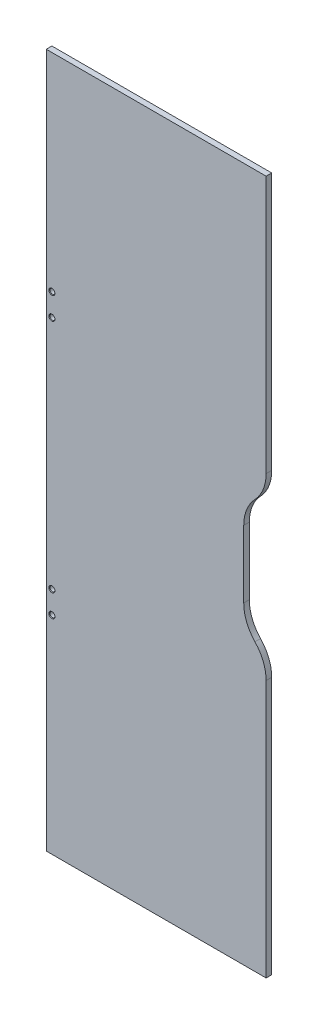
SolidWorks part; units mm, degrees
material "Beech"
ref_plane "Front Plane" through (0, 0, 0) normal (0, 0, 1) x (1, 0, 0)
ref_plane "Top Plane" through (0, 0, 0) normal (0, 1, 0) x (1, 0, 0)
ref_plane "Right Plane" through (0, 0, 0) normal (1, 0, 0) x (0, 0, -1)
sketch "Sketch1" plane through (0, 0, 0) normal (0, 0, 1) x (1, 0, 0)
  line L0 (55.499, 787.4) -> (55.499, 0) construction
  line L1 (42.799, 0) -> (292.1, 0)
  line L2 (42.799, 0) -> (42.799, 787.4)
  line L3 (42.799, 787.4) -> (292.1, 787.4)
  line L4 (292.1, 0) -> (292.1, 787.4)
  line L5 (38.1, 787.4) -> (38.1, 0) construction
  dimension "D1" = 292.1
  dimension "D2" = 787.4
  dimension "D3" = 38.1
  dimension "D4" = 17.399
  dimension "D5" = 12.7
extrude "Boss-Extrude1" add sketch "Sketch1" along normal blind 6.35
hole_wizard "#10 Clearance Hole1" positions "Sketch2" profile "Sketch3" hole size "#10" standard "ANSI Inch" end condition through all
sketch "Sketch2" plane through (0, 0, 6.35) normal (0, 0, 1) x (1, 0, 0)
  line L1 (42.799, 558.8) -> (55.499, 558.8) construction
  line L2 (42.799, 558.8) -> (42.799, 520.7) construction
  line L3 (42.799, 520.7) -> (55.499, 520.7) construction
  line L4 (55.499, 558.8) -> (55.499, 520.7) construction
  line L7 (42.799, 266.7) -> (55.499, 266.7) construction
  line L8 (42.799, 266.7) -> (42.799, 228.6) construction
  line L9 (42.799, 228.6) -> (55.499, 228.6) construction
  line L10 (55.499, 266.7) -> (55.499, 228.6) construction
  line L11 (42.799, 787.4) -> (42.799, 0) construction
  line L12 (292.1, 787.4) -> (42.799, 787.4) construction
  line L14 (49.149, 552.45) -> (49.149, 527.05) construction
  line L16 (49.149, 260.35) -> (49.149, 234.95) construction
  point P0 (49.149, 552.45)
  point P2 (49.149, 527.05)
  point P4 (49.149, 260.35)
  point P6 (49.149, 234.95)
  point P82 (49.149, 228.6)
  point P84 (42.799, 247.65)
  point P85 (49.149, 247.65)
  point P86 (42.799, 539.75)
  point P87 (49.149, 539.75)
  dimension "D1" = 228.6
  dimension "D2" = 228.6
  dimension "D3" = 6.35
  dimension "D4" = 12.7
  dimension "D5" = 38.1
sketch "Sketch3" plane through (49.149, 552.45, 6.35) normal (1, 0, 0) x (0, -1, 0)
  line L0 (0, 0) -> (0, 6.35)
  line L1 (0, 6.35) -> (2.8067, 6.35)
  line L2 (2.8067, 6.35) -> (2.8067, 0.635)
  line L3 (2.8067, 0.635) -> (3.4417, 0)
  line L5 (3.4417, 0) -> (0, 0)
  line L6 (-2.8067, 0.635) -> (-3.4417, 0) construction
  line L11 (0, -6.35) -> (0, 107.95) construction
  dimension "Thru Hole Dia." = 5.6134
  dimension "Thru Hole Depth" = 6.35
  dimension "Near C'Sink Dia." = 6.8834
  dimension "Near C'Sink Angle" = 90
hole_wizard "#10 Clearance Hole2" positions "Sketch4" profile "Sketch5" hole size "#10" standard "ANSI Inch"
sketch "Sketch4" plane through (0, 0, 6.35) normal (0, 0, 1) x (1, 0, 0)
  line L0 (266.7, 444.5) -> (266.7, 342.9) construction
  line L2 (292.1, 0) -> (292.1, 787.4) construction
  point P0 (266.7, 444.5)
  point P2 (266.7, 342.9)
  point P10 (292.1, 393.7)
  point P11 (266.7, 393.7)
  dimension "D1" = 101.6
  dimension "D2" = 25.4
sketch "Sketch5" plane through (266.7, 444.5, 6.35) normal (1, 0, 0) x (0, -1, 0)
  line L0 (0, 0) -> (0, 6.35)
  line L1 (0, 6.35) -> (2.8067, 6.35)
  line L2 (2.8067, 6.35) -> (2.8067, 0.635)
  line L3 (2.8067, 0.635) -> (3.4417, 0)
  line L5 (3.4417, 0) -> (0, 0)
  line L6 (-2.8067, 0.635) -> (-3.4417, 0) construction
  line L11 (0, -6.35) -> (0, 107.95) construction
  dimension "Thru Hole Dia." = 5.6134
  dimension "Thru Hole Depth" = 6.35
  dimension "Near C'Sink Dia." = 6.8834
  dimension "Near C'Sink Angle" = 90
sketch "Sketch6" plane through (0, 0, 6.35) normal (0, 0, 1) x (1, 0, 0)
  line L0 (292.1, 495.3) -> (304.8, 495.3)
  line L1 (292.1, 0) -> (292.1, 787.4) construction
  line L2 (304.8, 495.3) -> (304.8, 292.1)
  line L3 (304.8, 292.1) -> (292.1, 292.1)
  line L4 (266.7, 355.6) -> (266.7, 431.8)
  arc A0 (292.1, 292.1) -> (279.4, 323.85) centre (246.0625, 292.1) ccw
  arc A1 (279.4, 323.85) -> (266.7, 355.6) centre (312.7375, 355.6) cw
  arc A2 (266.7, 431.8) -> (279.4, 463.55) centre (312.7375, 431.8) cw
  arc A3 (279.4, 463.55) -> (292.1, 495.3) centre (246.0625, 495.3) ccw
  point P14 (0, 0)
  point P15 (292.1, 393.7)
  point P16 (266.7, 393.7)
  point P17 (304.8, 393.7)
  dimension "D1" = 25.4
  dimension "D2" = 12.7
  dimension "D3" = 76.2
  dimension "D4" = 203.2
extrude "Cut-Extrude1" cut sketch "Sketch6" against normal through all
